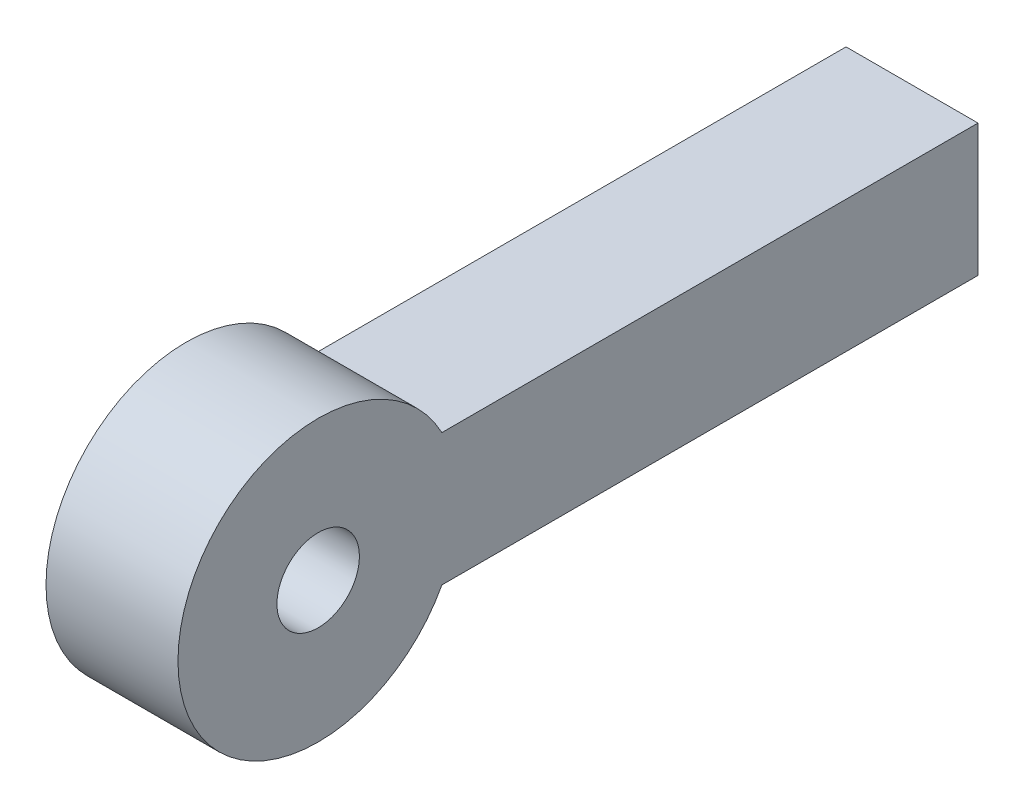
SolidWorks part; units mm, degrees
ref_plane "Ön Düzlem" through (0, 0, 0) normal (0, 0, 1) x (1, 0, 0)
ref_plane "Üst Düzlem" through (0, 0, 0) normal (0, 1, 0) x (1, 0, 0)
ref_plane "Sağ Düzlem" through (0, 0, 0) normal (1, 0, 0) x (0, 0, -1)
sketch "Çizim1" plane through (0, 0, 0) normal (1, 0, 0) x (0, 0, -1)
  line L0 (8, -0.8) -> (1.5, -0.8)
  line L1 (0, 0) -> (8, 0) construction
  line L2 (8, 0.8) -> (8, -0.8)
  line L3 (8, 0.8) -> (1.5, 0.8)
  circle A0 centre (0, 0) radius 0.5
  circle A1 centre (0, 0) radius 1.7
  point P10 (8, 0)
  dimension "D1" = 1
  dimension "D2" = 1.2
  dimension "D3" = 1.6
  dimension "D4" = 8
extrude "Yükseklik-Ekstrüzyon1" add sketch "Çizim1" along normal blind 1.6
